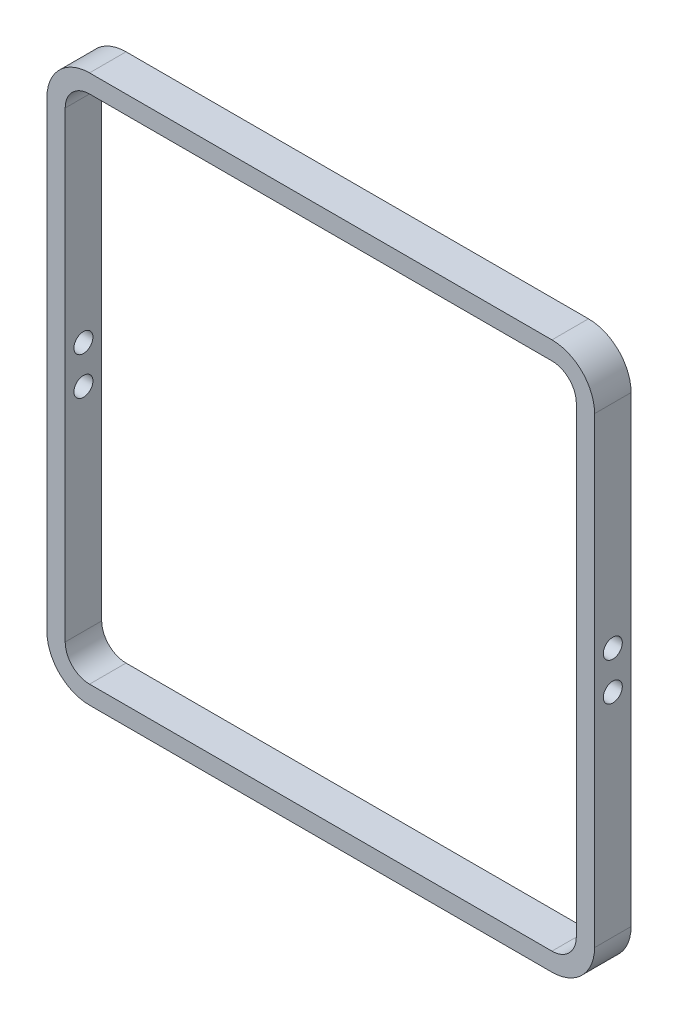
SolidWorks part; units mm, degrees
ref_plane "Front Plane" through (0, 0, 0) normal (1, 0, 0) x (0, 1, 0)
ref_plane "Top Plane" through (0, 0, 0) normal (0, 0, 1) x (0, 1, 0)
ref_plane "Right Plane" through (0, 0, 0) normal (0, 1, 0) x (-1, 0, 0)
sketch "Sketch1" plane through (0, 0, 0) normal (0, 0, 1) x (0, 1, 0)
  line L1 (-112.5, -112.5) -> (112.5, -112.5)
  line L2 (-112.5, -112.5) -> (-112.5, 112.5)
  line L3 (-112.5, 112.5) -> (112.5, 112.5)
  line L4 (112.5, -112.5) -> (112.5, 112.5)
  line L5 (-112.5, -112.5) -> (112.5, 112.5) construction
  line L6 (-112.5, 112.5) -> (112.5, -112.5) construction
  line L7 (-105, -105) -> (105, -105)
  line L8 (-105, -105) -> (-105, 105)
  line L9 (-105, 105) -> (105, 105)
  line L10 (105, -105) -> (105, 105)
  line L11 (-105, -105) -> (105, 105) construction
  line L12 (-105, 105) -> (105, -105) construction
  point P0 (0, 0)
  point P5 (0, 0)
  dimension "D1" = 225
  dimension "D2" = 210
extrude "Boss-Extrude1" add sketch "Sketch1" along normal blind 15
sketch "Sketch2" plane through (112.5, 0, 0) normal (1, 0, 0) x (0, 1, 0)
  line L0 (-112.5, 15) -> (-112.5, 0) construction
  line L1 (-112.5, 0) -> (-112.5, 7.5) construction
  line L2 (-112.5, 7.5) -> (112.5, 7.5) construction
  line L3 (112.5, 15) -> (112.5, 0) construction
  line L4 (-112.5, 15) -> (0, 15) construction
  line L5 (-112.5, 15) -> (112.5, 15) construction
  line L6 (0, 15) -> (-56.25, 15) construction
  line L9 (0, 15) -> (0, 0) construction
  circle A1 centre (-7.8, 7.5) radius 3.9
  circle A2 centre (7.8, 7.5) radius 3.9
  point P25 (7.8, 7.5)
extrude "Cut-Extrude1" cut sketch "Sketch2" against normal through all
fillet "Fillet1" radius 10 4 edges at (105, 105, 7.5) (105, -105, 7.5) (-105, 105, 7.5) (-105, -105, 7.5)
fillet "Fillet2" radius 17.5 4 edges at (112.5, -112.5, 7.5) (-112.5, -112.5, 7.5) (112.5, 112.5, 7.5) (-112.5, 112.5, 7.5)
